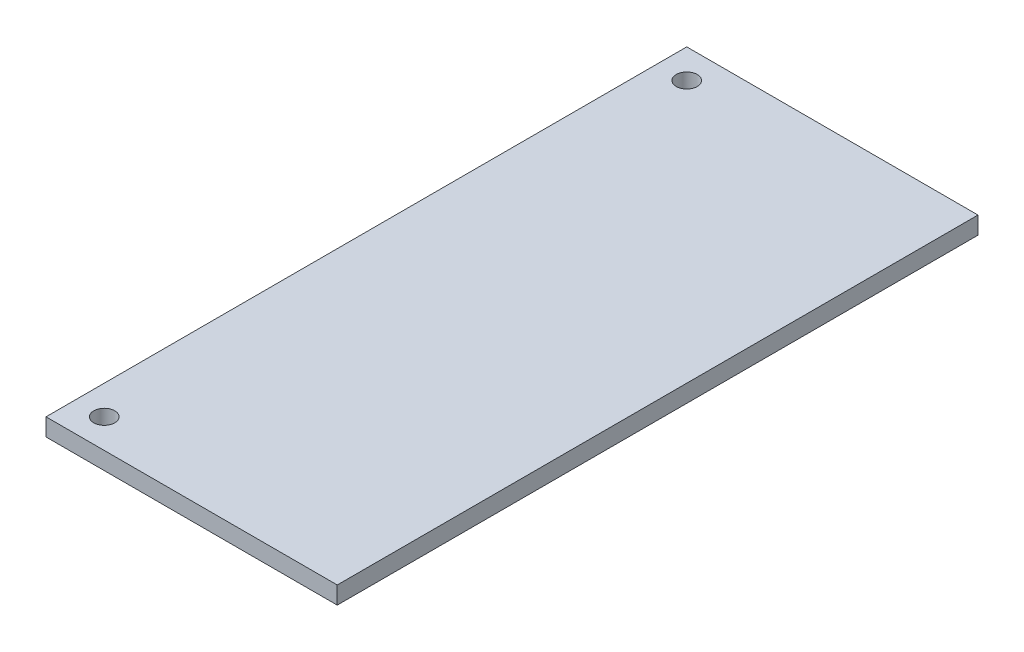
SolidWorks part; units mm, degrees
ref_plane "Front Plane" through (0, 0, 0) normal (0, 0, 1) x (1, 0, 0)
ref_plane "Top Plane" through (0, 0, 0) normal (0, 1, 0) x (1, 0, 0)
ref_plane "Right Plane" through (0, 0, 0) normal (1, 0, 0) x (0, 0, -1)
sketch "Sketch1" plane through (0, 0, 0) normal (0, 1, 0) x (1, 0, 0)
  line L1 (-25, -55) -> (25, -55)
  line L2 (-25, -55) -> (-25, 55)
  line L3 (-25, 55) -> (25, 55)
  line L4 (25, -55) -> (25, 55)
  line L5 (-25, -55) -> (25, 55) construction
  line L6 (-25, 55) -> (25, -55) construction
  point P0 (0, 0)
  point P6 (-47.0129, 16.3281)
  dimension "D1" = 50
  dimension "D2" = 110
extrude "Boss-Extrude1" add sketch "Sketch1" along normal blind 3
sketch "Sketch2" plane through (0, 3, 0) normal (0, 1, 0) x (1, 0, 0)
  line L0 (-25, 55) -> (-25, -55) construction
  line L1 (25, 55) -> (-25, 55) construction
  line L2 (-25, -55) -> (25, -55) construction
  point P0 (-20, 50)
  point P2 (-20, -50)
  dimension "D1" = 5
  dimension "D2" = 5
  dimension "D3" = 5
hole_wizard "M3 Clearance Hole1" positions "Sketch2" profile "Sketch3" hole size "M3" standard "ANSI Metric"
sketch "Sketch3" plane through (-20, 3, -50) normal (1, 0, 0) x (0, 0, 1)
  line L0 (0, 0) -> (0, 7.0815)
  line L1 (0, 7.0815) -> (1.8, 6)
  line L2 (1.8, 6) -> (1.8, 0)
  line L5 (1.8, 0) -> (0, 0)
  line L10 (0, 7.0815) -> (-1.8, 6) construction
  line L11 (0, -6.35) -> (0, 107.95) construction
  dimension "Hole Dia." = 3.6
  dimension "Hole Depth" = 6
  dimension "Drill Angle" = 118
